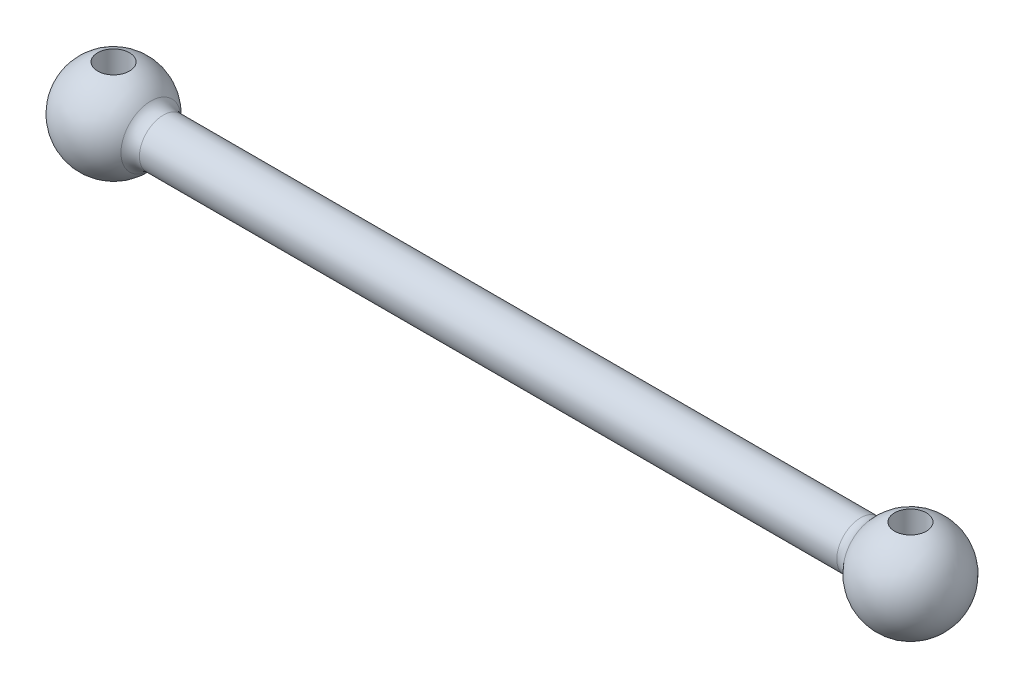
SolidWorks part; units mm, degrees
material "Cast Alloy Steel"
ref_plane "Front" through (0, 0, 0) normal (0, 0, 1) x (1, 0, 0)
ref_plane "Top" through (0, 0, 0) normal (0, 1, 0) x (1, 0, 0)
ref_plane "Right" through (0, 0, 0) normal (1, 0, 0) x (0, 0, -1)
sketch "Sketch1" plane through (0, 0, 0) normal (0, 0, 1) x (1, 0, 0)
  line L0 (23, 0) -> (28, 0)
  line L1 (0, 0) -> (23, 0)
  line L2 (0, 0) -> (0, 1.5)
  line L3 (0, 1.5) -> (23, 1.5)
  line L4 (23, 0) -> (23, 1.5)
  arc A0 (28, 0) -> (22.4019, 1.5) centre (25, 0) ccw
  point P5 (25, 0)
  dimension "D1" = 23
  dimension "D2" = 1.5
  dimension "D3" = 5
  dimension "D4" = 3
revolve "Revolve2" add sketch "Sketch1" angle 360 about L1
ref_plane "Plane1" through (0, 3, 0) normal (0, 1, 0) x (1, 0, 0)
sketch "Sketch2" plane through (0, 3, 0) normal (0, 1, 0) x (1, 0, 0)
  line L0 (0, 0) -> (31.1755, 0) construction
  circle A0 centre (25, 0) radius 1
  dimension "D1" = 25
extrude "Cut-Extrude1" cut sketch "Sketch2" against normal through all
mirror "Mirror1" about plane through (0, 0, 0) normal (-1, 0, 0) of "Cut-Extrude1", "Revolve2"
fillet "Fillet1" radius 1 1 edges at (22.4019, 0, 1.5)
fillet "Fillet2" radius 1 1 edges at (-22.4019, 0, 1.5)
